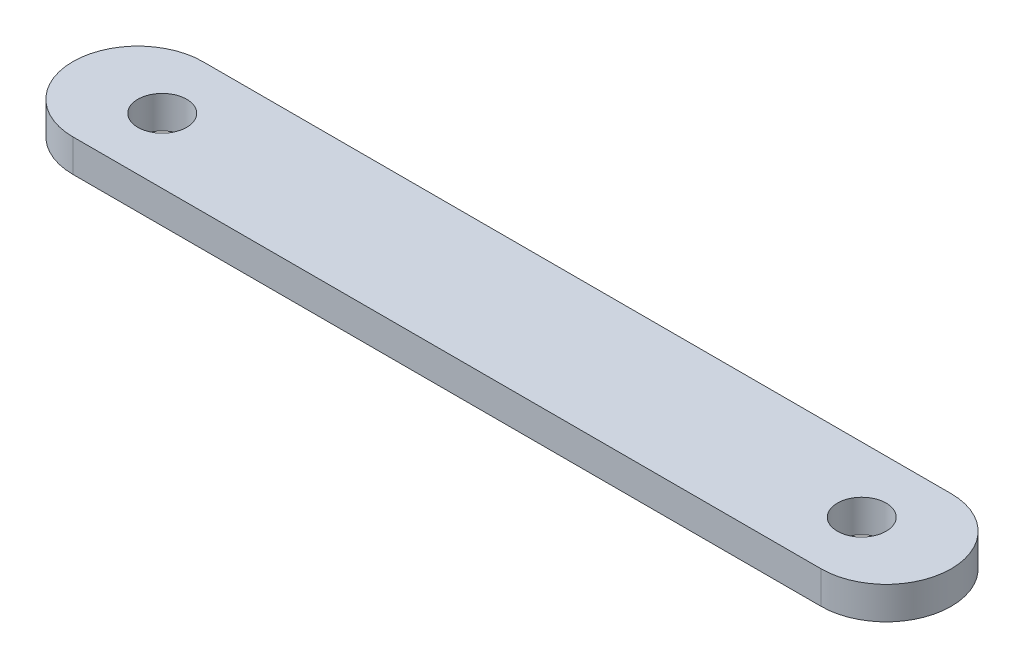
SolidWorks part; units mm, degrees
ref_plane "Front Plane" through (0, 0, 0) normal (0, 0, 1) x (1, 0, 0)
ref_plane "Top Plane" through (0, 0, 0) normal (0, 1, 0) x (1, 0, 0)
ref_plane "Right Plane" through (0, 0, 0) normal (1, 0, 0) x (0, 0, -1)
sketch "Sketch1" plane through (0, 0, 0) normal (0, 1, 0) x (1, 0, 0)
  line L1 (1150, -200) -> (-1150, -200)
  line L2 (1150, -200) -> (1150, 200)
  line L3 (1150, 200) -> (-1150, 200)
  line L4 (-1150, -200) -> (-1150, 200)
  line L5 (1150, -200) -> (-1150, 200) construction
  line L6 (1150, 200) -> (-1150, -200) construction
  arc A0 (-1150, 200) -> (-1150, -200) centre (-1150, 0) ccw
  arc A1 (1150, 200) -> (1150, -200) centre (1150, 0) cw
  circle A2 centre (-1075, 0) radius 75
  circle A3 centre (1075, 0) radius 75
  point P0 (0, 0)
  dimension "D3" = 150
  dimension "D6" = 150
  dimension "D1" = 400
  dimension "D2" = 2300
  dimension "D4" = 1075
  dimension "D5" = 1075
  dimension "D7" = 200
  dimension "D8" = 200
extrude "Boss-Extrude1" add sketch "Sketch1" along normal blind 100 contours L4 A0 | L2 A3 L3 L4 A2 L1 | A1 L2
